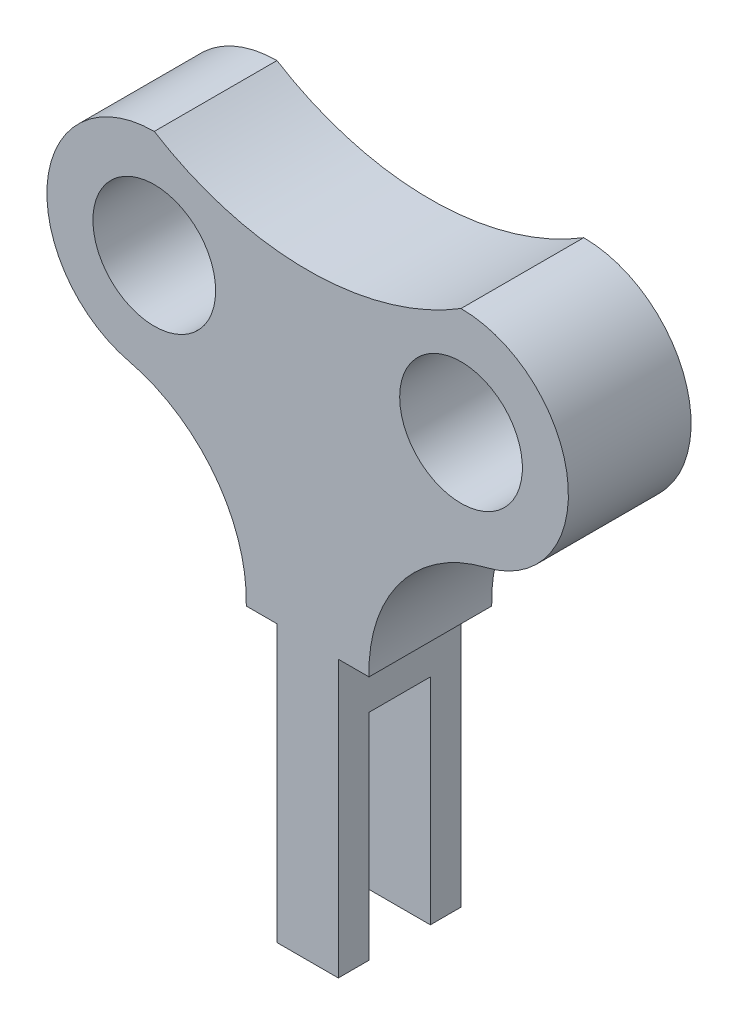
SolidWorks part; units mm, degrees
ref_plane "Front Plane" through (0, 0, 0) normal (0, 0, 1) x (1, 0, 0)
ref_plane "Top Plane" through (0, 0, 0) normal (0, 1, 0) x (1, 0, 0)
ref_plane "Right Plane" through (0, 0, 0) normal (1, 0, 0) x (0, 0, -1)
sketch "Sketch1" plane through (0, 0, 0) normal (0, 0, 1) x (1, 0, 0)
  line L0 (0, 58) -> (0, -42) construction
  line L1 (-25, 0) -> (25, 0) construction
  line L2 (-25, 0) -> (-25, 17.5) construction
  line L3 (25, 0) -> (25, 17.5) construction
  line L4 (-25, 0) -> (-34.9905, -41.3091) construction
  line L5 (5, -42) -> (10, -42)
  line L6 (-5, -87) -> (5, -87)
  line L7 (-5, -87) -> (-5, -42)
  line L8 (-10, -42) -> (-5, -42)
  line L10 (5, -87) -> (5, -42)
  line L11 (-5, -87) -> (5, -42) construction
  line L12 (-5, -42) -> (5, -87) construction
  circle A0 centre (-25, 0) radius 10
  arc A1 (-25, 17.5) -> (-29.1137, -17.0096) centre (-25, 0) ccw
  arc A2 (-25, 17.5) -> (25, 17.5) centre (0, 58) ccw
  arc A3 (25, 17.5) -> (29.1137, -17.0096) centre (25, 0) cw
  circle A4 centre (25, 0) radius 10
  arc A7 (-10, -42) -> (-29.1137, -17.0096) centre (-34.9905, -41.3091) ccw
  arc A9 (10, -42) -> (29.1137, -17.0096) centre (34.9905, -41.3091) cw
  point P16 (0, -64.5)
  dimension "D2" = 100
  dimension "D3" = 10
  dimension "D4" = 42
  dimension "D1" = 50
  dimension "D5" = 20
  dimension "D6" = 45
extrude "Boss-Extrude1" add sketch "Sketch1" along normal blind 20
sketch "Sketch2" plane through (5, 0, 0) normal (1, 0, 0) x (0, 0, -1)
  line L0 (-20, -87) -> (0, -87) construction
  line L1 (-15, -52) -> (-5, -52)
  line L2 (-15, -52) -> (-15, -87)
  line L4 (-5, -52) -> (-5, -87)
  line L5 (-15, -52) -> (-10, -87) construction
  line L6 (-10, -87) -> (-5, -52) construction
  line L9 (-10, -44.9605) -> (-10, -87) construction
  line L10 (-15, -87) -> (-5, -87)
  point P0 (-10, -87)
  dimension "D1" = 35
  dimension "D2" = 10
extrude "Cut-Extrude1" cut sketch "Sketch2" against normal up to surface (10 mm away) up to face at (-5, -64.5, 10)
